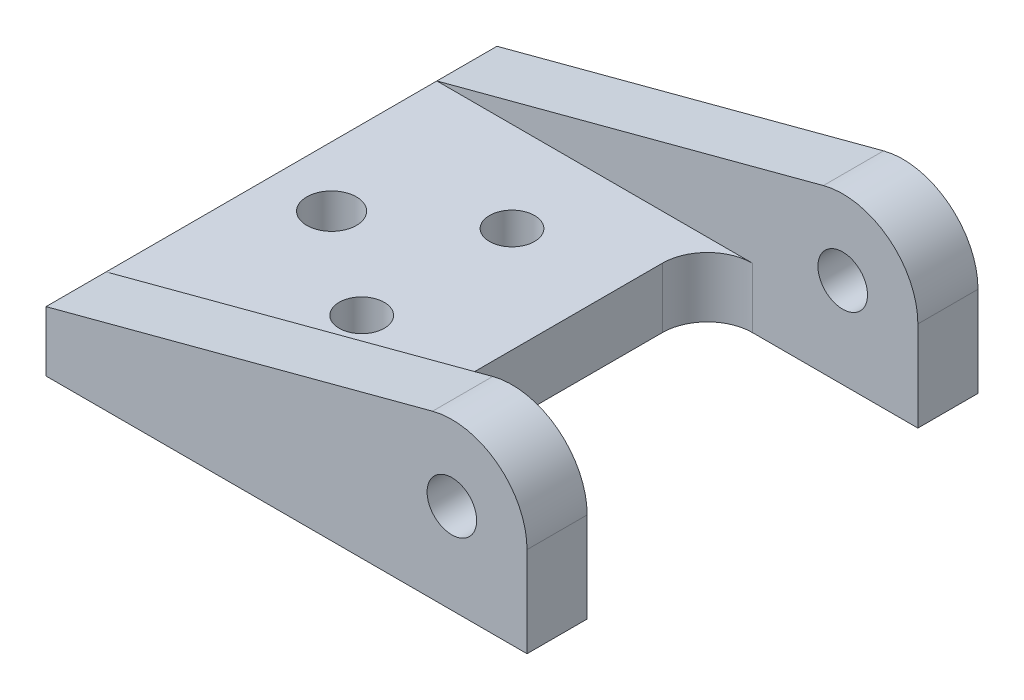
SolidWorks part; units mm, degrees
material "6061 合金"
ref_plane "前视基准面" through (0, 0, 0) normal (0, 0, 1) x (1, 0, 0)
ref_plane "上视基准面" through (0, 0, 0) normal (0, 1, 0) x (1, 0, 0)
ref_plane "右视基准面" through (0, 0, 0) normal (1, 0, 0) x (0, 0, -1)
sketch "草图1" plane through (0, 0, 0) normal (0, 0, 1) x (1, 0, 0)
  line L0 (0, 0) -> (32, 0)
  line L1 (32, 0) -> (32, 6)
  line L3 (25.7161, 10.8324) -> (0, 4)
  line L4 (0, 4) -> (0, 0)
  arc A0 (32, 6) -> (25.7161, 10.8324) centre (27, 6) ccw
  circle A1 centre (27, 6) radius 1.65
  dimension "D3" = 10
  dimension "D4" = 3.3
  dimension "D1" = 32
  dimension "D2" = 6
  dimension "D5" = 4
extrude "凸台-拉伸1" add sketch "草图1" along normal blind 30
sketch "草图2" plane through (0, 0, 0) normal (0, -1, 0) x (1, 0, 0)
  line L0 (32, 30) -> (32, 0) construction
  line L1 (32, 4) -> (18, 4)
  line L2 (32, 4) -> (32, 26)
  line L3 (32, 26) -> (18, 26)
  line L4 (18, 4) -> (18, 26)
  line L5 (0, 30) -> (32, 30) construction
  line L6 (0, 0) -> (32, 0) construction
  dimension "D1" = 4
  dimension "D2" = 4
  dimension "D3" = 14
extrude "切除-拉伸1" cut sketch "草图2" against normal blind 30
ref_plane "基准面1" through (0, 4, 0) normal (0, -1, 0) x (-1, 0, 0)
sketch "草图3" plane through (0, 4, 0) normal (0, -1, 0) x (-1, 0, 0)
  line L0 (0, -30) -> (0, 0) construction
  line L1 (-18, -4) -> (0, -4)
  line L2 (-18, -4) -> (-18, -26)
  line L3 (-18, -26) -> (0, -26)
  line L4 (0, -4) -> (0, -26)
  line L5 (-32, -26) -> (-18, -26) construction
extrude "切除-拉伸2" cut sketch "草图3" against normal blind 30
fillet "圆角1" radius 3 2 edges at (18, 2, 26) (18, 2, 4)
sketch "草图4" plane through (0, 4, 0) normal (0, 1, 0) x (1, 0, 0)
  line L0 (0, -4) -> (21, -4) construction
  line L1 (0, -26) -> (0, -4) construction
  line L2 (4, -15) -> (18, -15) construction
  circle A0 centre (4, -15) radius 1.65
  dimension "D1" = 3.3
  dimension "D3" = 4
  dimension "D5" = 11
extrude "切除-拉伸3" cut sketch "草图4" against normal blind 30
sketch "草图5" plane through (0, 4, 0) normal (0, 1, 0) x (1, 0, 0)
  line L0 (18, -15) -> (4, -15) construction
  line L1 (11, -10) -> (11, -20) construction
  circle A0 centre (11, -10) radius 1.5
  circle A1 centre (11, -20) radius 1.5
  point P7 (11, -15)
  dimension "D1" = 3
  dimension "D2" = 3
extrude "切除-拉伸4" cut sketch "草图5" against normal through all
